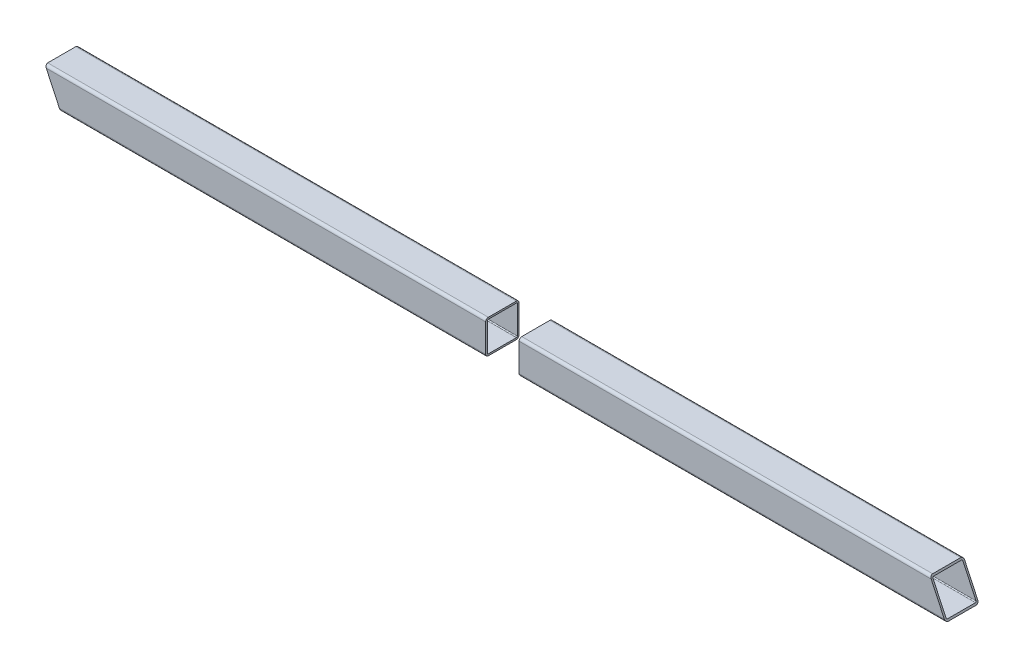
SolidWorks part; units mm, degrees
material "Plain Carbon Steel"
ref_plane "Front Plane" through (0, 0, 0) normal (0, 0, 1) x (1, 0, 0)
ref_plane "Top Plane" through (0, 0, 0) normal (0, 1, 0) x (1, 0, 0)
ref_plane "Right Plane" through (0, 0, 0) normal (1, 0, 0) x (0, 0, -1)
sketch "Sketch1" plane through (0, 0, 0) normal (1, 0, 0) x (0, 0, -1)
  line L0 (0, 2.54) -> (0, 29.21)
  line L1 (-2.54, 31.75) -> (-29.21, 31.75)
  line L2 (-31.75, 29.21) -> (-31.75, 2.54)
  line L3 (-29.21, 0) -> (-2.54, 0)
  line L4 (-1.651, 2.54) -> (-1.651, 29.21)
  line L5 (-2.54, 30.099) -> (-29.21, 30.099)
  line L6 (-30.099, 29.21) -> (-30.099, 2.54)
  line L7 (-29.21, 1.651) -> (-2.54, 1.651)
  arc A0 (-31.75, 2.54) -> (-29.21, 0) centre (-29.21, 2.54) ccw
  arc A1 (0, 2.54) -> (-2.54, 0) centre (-2.54, 2.54) cw
  arc A2 (0, 29.21) -> (-2.54, 31.75) centre (-2.54, 29.21) ccw
  arc A3 (-31.75, 29.21) -> (-29.21, 31.75) centre (-29.21, 29.21) cw
  arc A4 (-1.651, 29.21) -> (-2.54, 30.099) centre (-2.54, 29.21) ccw
  arc A5 (-30.099, 29.21) -> (-29.21, 30.099) centre (-29.21, 29.21) cw
  arc A6 (-30.099, 2.54) -> (-29.21, 1.651) centre (-29.21, 2.54) ccw
  arc A7 (-1.651, 2.54) -> (-2.54, 1.651) centre (-2.54, 2.54) cw
  point P12 (0, 0)
  point P15 (0, 31.75)
  point P18 (-31.75, 31.75)
  dimension "D3" = 2.54
  dimension "D1" = 31.75
  dimension "D2" = 31.75
  dimension "D4" = 1.651
extrude "Boss-Extrude1" add sketch "Sketch1" along normal blind 393.7
scale "Scale1" scale about centroid uniform scaling no x scale factor 1 y scale factor 0.4 z scale factor 0.4
sketch "Sketch2" plane through (0, 0, 22.225) normal (0, 0, 1) x (1, 0, 0)
  line L0 (0, 22.225) -> (5.9221, 9.525)
  line L1 (393.7, 9.525) -> (0, 9.525) construction
  line L2 (5.9221, 9.525) -> (0, 9.525)
  line L3 (0, 9.525) -> (0, 22.225)
  line L4 (336.3096, 22.225) -> (342.2317, 9.525)
  line L5 (393.7, 22.225) -> (0, 22.225) construction
  line L6 (191.6712, 332.403) -> (486.8701, -300.653) construction
  line L7 (342.2317, 9.525) -> (360.9056, 9.525)
  line L8 (360.9056, 9.525) -> (360.9056, 22.225)
  line L9 (360.9056, 22.225) -> (336.3096, 22.225)
  line L15 (167.4611, 321.1136) -> (167.4611, -324.6648) construction
  line L16 (167.4611, 22.225) -> (180.1611, 22.225)
  line L18 (167.4611, 22.225) -> (167.4611, 9.525)
  line L19 (167.4611, 9.525) -> (180.1611, 9.525)
  line L20 (180.1611, 22.225) -> (180.1611, 9.525)
  line L21 (180.1611, 327.0357) -> (180.1611, -323.6638) construction
  point P16 (339.2706, 15.875)
  dimension "D1" = 25
extrude "Cut-Extrude1" cut sketch "Sketch2" against normal through all
